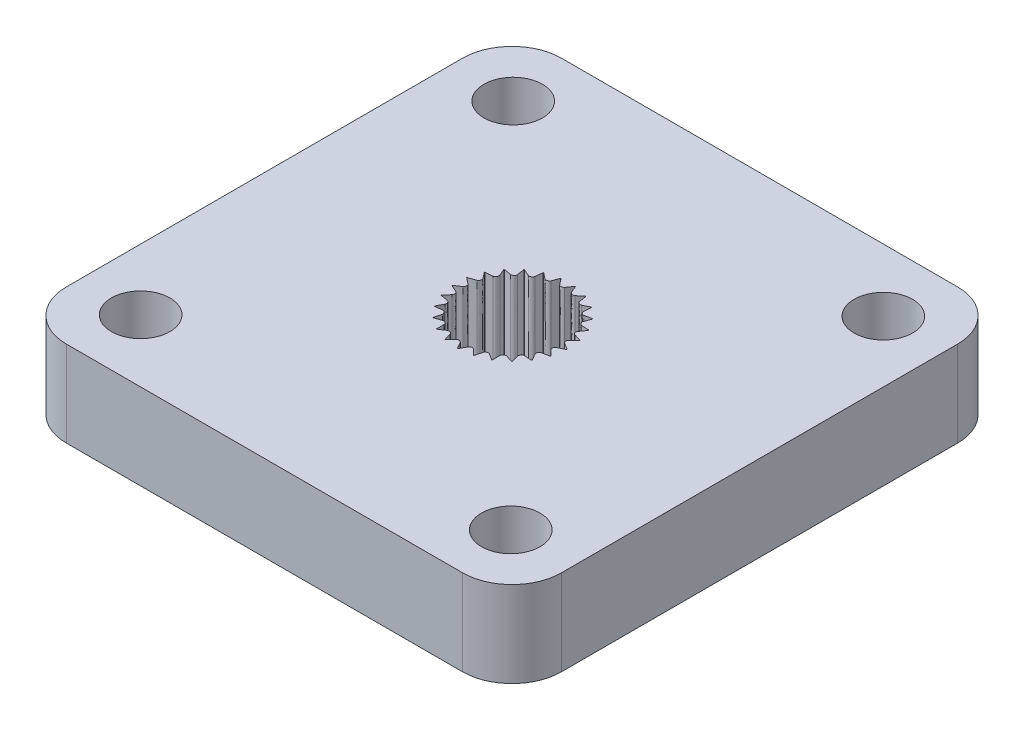
SolidWorks part; units mm, degrees
ref_plane "Front Plane" through (0, 0, 0) normal (0, 0, 1) x (1, 0, 0)
ref_plane "Top Plane" through (0, 0, 0) normal (0, 1, 0) x (1, 0, 0)
ref_plane "Right Plane" through (0, 0, 0) normal (1, 0, 0) x (0, 0, -1)
sketch "Sketch1" plane through (0, 0, 0) normal (0, 1, 0) x (1, 0, 0)
  line L1 (0, 0) -> (50.2429, 0)
  line L2 (0, 0) -> (0, 34.9455)
  line L3 (0, 34.9455) -> (50.2429, 34.9455)
  line L4 (50.2429, 0) -> (50.2429, 34.9455)
  line L5 (0, 0) -> (50.2429, 34.9455) construction
  line L6 (0, 34.9455) -> (50.2429, 0) construction
  point P4 (25.1215, 17.4728)
extrude "Boss-Extrude1" add sketch "Sketch1" along normal blind 4.4
extrude "Cut-Extrude2" cut sketch "Sketch4" against normal through all flip side to cut
sketch "Sketch4" plane through (166.0463, 0, -236.0281) normal (0, -1, 0) x (0, 0, 1)
  line L1 (208.0298, 152.713) -> (233.4298, 152.713)
  line L2 (208.0298, 152.713) -> (208.0298, 127.313)
  line L3 (208.0298, 127.313) -> (233.4298, 127.313)
  line L4 (233.4298, 152.713) -> (233.4298, 127.313)
  line L5 (208.0298, 152.713) -> (233.4298, 127.313) construction
  line L6 (208.0298, 127.313) -> (233.4298, 152.713) construction
  point P0 (220.7298, 140.013)
  point P6 (220.7298, 140.013)
fillet "Fillet1" radius 2.54 4 edges at (38.7333, 2.2, -2.5983) (13.3333, 2.2, -2.5983) (38.7333, 2.2, -27.9983) (13.3333, 2.2, -27.9983)
extrude "Cut-Extrude5" cut sketch "Sketch8" against normal through all
sketch "Sketch8" plane through (166.0463, 4.4, 928.4707) normal (0, 1, 0) x (0, 0, -1)
  circle A4 centre (934.213, 130.5192) radius 1.5
  circle A5 centre (953.2629, 130.457) radius 1.5
  circle A6 centre (934.2752, 149.5691) radius 1.5
  circle A7 centre (953.3251, 149.5069) radius 1.5
extrude "Cut-Extrude15" cut sketch "Sketch18" against normal through all and the other way through all contours S310 S311 L17 L18 L21 S146 L22 L38 L39 S147 S148 S149 L43 S150 S232 S233 L44 S235 S236 S237 L46 S239 S240 S241 S242 S243 S244 S245 S246 S247 S248 S249 S250 S251 S252 S253 S254 S255 S256 S257 S258 S259 L47 S260 S261 S262 L52 S263 S264 S265 L53
sketch "Sketch18" plane through (170.1582, 0, -5.4879) normal (0, -1, 0) x (0, 0, 1)
  line L0 (-8.9191, 146.9066) -> (-9.2331, 146.6211)
  line L1 (-9.6448, 147.0479) -> (-9.8788, 146.6937)
  line L2 (-10.3828, 147.0042) -> (-10.5223, 146.6034)
  line L3 (-12.4352, 144.0663) -> (-12.7769, 143.8287)
  line L4 (-12.3448, 143.423) -> (-12.6158, 143.1072)
  line L5 (-12.0972, 142.8224) -> (-12.2804, 142.4485)
  line L6 (-11.1062, 141.4416) -> (-10.7643, 141.6794)
  line L7 (-10.404, 141.2106) -> (-10.133, 141.5263)
  line L12 (-9.6665, 141.1614) -> (-9.4834, 141.5351)
  line L13 (-7.2766, 144.4621) -> (-6.9625, 144.7477)
  line L14 (-7.4468, 145.0892) -> (-7.2127, 145.4433)
  line L15 (-7.7676, 145.6543) -> (-7.6281, 146.0549)
  line L16 (-8.7558, 146.4912) -> (-8.7333, 146.5199)
  line L17 (-7.8155, 145.671) -> (-7.686, 146.0432)
  line L18 (-7.7007, 146.0594) -> (-7.686, 146.0432)
  line L21 (-8.0827, 145.9662) -> (-7.7007, 146.0594)
  line L22 (-8.2695, 146.1262) -> (-8.2358, 146.5183)
  line L23 (-8.6257, 146.3902) -> (-8.2513, 146.5893)
  line L25 (-10.4149, 147.0375) -> (-10.564, 146.609) construction
  line L26 (-12.4579, 144.097) -> (-12.8238, 143.8425) construction
  line L27 (-12.3771, 143.4451) -> (-12.6672, 143.107) construction
  line L28 (-12.1366, 142.8337) -> (-12.3326, 142.4335) construction
  line L29 (-11.0949, 141.3721) -> (-10.729, 141.6267) construction
  line L30 (-10.3783, 141.1442) -> (-10.0881, 141.4822) construction
  line L31 (-9.6275, 141.1015) -> (-9.4315, 141.5017) construction
  line L32 (-7.2361, 144.4135) -> (-6.9003, 144.7188) construction
  line L33 (-7.3981, 145.0502) -> (-7.1478, 145.4289) construction
  line L34 (-7.7133, 145.6266) -> (-7.5642, 146.0551) construction
  line L35 (-8.7158, 146.4598) -> (-8.6933, 146.4885) construction
  line L36 (-9.6647, 147.0894) -> (-9.9149, 146.7107) construction
  line L37 (-8.9252, 146.953) -> (-9.261, 146.6477) construction
  line L38 (-8.2541, 146.5303) -> (-8.2358, 146.5183)
  line L39 (-8.6019, 146.3454) -> (-8.2541, 146.5303)
  line L40 (-8.2188, 146.1219) -> (-8.1826, 146.544)
  line L43 (-8.9069, 146.849) -> (-9.1989, 146.5835)
  line L44 (-9.6188, 146.9951) -> (-9.8365, 146.6657)
  line L45 (-8.0948, 146.0155) -> (-7.6834, 146.1159)
  line L46 (-10.3446, 146.9595) -> (-10.4743, 146.5867)
  line L47 (-12.4062, 144.0247) -> (-12.7234, 143.804)
  line L49 (-8.2513, 146.5893) -> (-8.1826, 146.544)
  line L51 (-7.6834, 146.1159) -> (-7.6281, 146.0549)
  line L52 (-12.3062, 143.3899) -> (-12.5579, 143.0967)
  line L53 (-12.0516, 142.8) -> (-12.2217, 142.4528)
  line L54 (-11.1108, 141.5002) -> (-10.7934, 141.7211)
  line L55 (-10.4232, 141.2662) -> (-10.1715, 141.5594)
  line L56 (-9.699, 141.2105) -> (-9.529, 141.5574)
  line L57 (-7.3108, 144.4997) -> (-7.0186, 144.7653)
  line L58 (-7.4891, 145.1172) -> (-7.2715, 145.4465)
  ellipse E1 centre (-9.8345, 144.0943) end of major axis (-12.1937, 145.9474) minor radius 2.9998 (-8.7897, 146.9063) -> (-8.9252, 146.953) ccw construction
  ellipse E26 centre (-9.8345, 144.0943) end of major axis (-7.4752, 142.2412) minor radius 2.9998 (-11.649, 146.4833) -> (-11.761, 146.394) ccw construction
  ellipse E27 centre (-9.8345, 144.0943) end of major axis (-12.1937, 145.9474) minor radius 2.9998 (-12.1861, 145.9571) -> (-12.2724, 145.8426) ccw construction
  ellipse E28 centre (-9.8345, 144.0943) end of major axis (-12.1937, 145.9474) minor radius 2.9998 (-12.5754, 145.3137) -> (-12.6305, 145.1815) ccw construction
  ellipse E29 centre (-9.8345, 144.0943) end of major axis (-12.1937, 145.9474) minor radius 2.9998 (-12.7925, 144.5938) -> (-12.813, 144.452) ccw construction
  ellipse E30 centre (-9.8345, 144.0943) end of major axis (-12.1937, 145.9474) minor radius 2.9998 (-12.8238, 143.8425) -> (-12.8084, 143.7) ccw construction
  ellipse E31 centre (-9.8345, 144.0943) end of major axis (-12.1937, 145.9474) minor radius 2.9998 (-12.6672, 143.107) -> (-12.6168, 142.9729) ccw construction
  ellipse E32 centre (-9.8345, 144.0943) end of major axis (-12.1937, 145.9474) minor radius 2.9998 (-12.3326, 142.4335) -> (-12.2505, 142.3161) ccw construction
  ellipse E33 centre (-9.8345, 144.0943) end of major axis (-7.4752, 142.2412) minor radius 2.9998 (-11.8411, 141.8644) -> (-11.7323, 141.7711) ccw construction
  ellipse E34 centre (-9.8345, 144.0943) end of major axis (-12.1937, 145.9474) minor radius 2.9998 (-11.2235, 141.4354) -> (-11.0949, 141.3721) ccw construction
  ellipse E35 centre (-9.8345, 144.0943) end of major axis (-12.1937, 145.9474) minor radius 2.9998 (-10.5186, 141.1735) -> (-10.3783, 141.1442) ccw construction
  ellipse E36 centre (-9.8345, 144.0943) end of major axis (-12.1937, 145.9474) minor radius 2.9998 (-9.7707, 141.0951) -> (-9.6275, 141.1015) ccw construction
  ellipse E37 centre (-9.8345, 144.0943) end of major axis (-12.1937, 145.9474) minor radius 2.9998 (-9.0268, 141.2051) -> (-8.8898, 141.247) ccw construction
  ellipse E38 centre (-9.8345, 144.0943) end of major axis (-12.1937, 145.9474) minor radius 2.9998 (-8.3337, 141.4967) -> (-8.2113, 141.5713) ccw construction
  ellipse E39 centre (-9.8345, 144.0943) end of major axis (-7.4752, 142.2412) minor radius 2.9998 (-7.7348, 141.9515) -> (-7.6349, 142.0542) ccw construction
  ellipse E40 centre (-9.8345, 144.0943) end of major axis (-7.4752, 142.2412) minor radius 2.9998 (-7.2679, 142.541) -> (-7.1967, 142.6653) ccw construction
  ellipse E41 centre (-9.8345, 144.0943) end of major axis (-7.4752, 142.2412) minor radius 2.9998 (-6.9623, 143.228) -> (-6.9242, 143.3661) ccw construction
  ellipse E42 centre (-9.8345, 144.0943) end of major axis (-12.1937, 145.9474) minor radius 2.9998 (-6.8371, 143.9695) -> (-6.8346, 144.1127) ccw construction
  ellipse E43 centre (-9.8345, 144.0943) end of major axis (-12.1937, 145.9474) minor radius 2.9998 (-6.9003, 144.7188) -> (-6.9335, 144.8582) ccw construction
  ellipse E44 centre (-9.8345, 144.0943) end of major axis (-12.1937, 145.9474) minor radius 2.9998 (-7.1478, 145.4289) -> (-7.2146, 145.5556) ccw construction
  ellipse E45 centre (-9.8345, 144.0943) end of major axis (-12.1937, 145.9474) minor radius 2.9998 (-7.5642, 146.0551) -> (-7.6604, 146.1613) ccw construction
  ellipse E46 centre (-9.8345, 144.0943) end of major axis (-12.1937, 145.9474) minor radius 2.9998 (-8.1232, 146.5581) -> (-8.2428, 146.637) ccw construction
  ellipse E47 centre (-9.8345, 144.0943) end of major axis (-12.1937, 145.9474) minor radius 2.9998 (-10.9979, 146.8595) -> (-11.1286, 146.8008) ccw construction
  ellipse E48 centre (-9.8345, 144.0943) end of major axis (-7.4752, 142.2412) minor radius 2.9998 (-10.2737, 147.0619) -> (-10.4149, 147.0375) ccw construction
  ellipse E49 centre (-9.8345, 144.0943) end of major axis (-12.1937, 145.9474) minor radius 2.9998 (-9.5219, 147.0778) -> (-9.6647, 147.0894) ccw construction
  spline S2 degree 3 poles (-10.729, 141.6267) (-10.7247, 141.6297) (-10.7196, 141.6322) (-10.7139, 141.6338) (-10.7098, 141.6349) (-10.7053, 141.6355) (-10.7007, 141.6355) (-10.6968, 141.6355) (-10.6927, 141.6351) (-10.6888, 141.6341) (-10.6848, 141.6332) (-10.6809, 141.6317) (-10.6773, 141.6298) (-10.6738, 141.628) (-10.6706, 141.6258) (-10.6678, 141.6234) (-10.664, 141.6201) (-10.6608, 141.6163) (-10.6583, 141.6125) (-10.6557, 141.6085) (-10.6538, 141.6044) (-10.6526, 141.6003) knots -0.000035 -0.000035 -0.000035 -0.000035 -0.000015 -0.000015 -0.000015 0 0 0 0.000012 0.000012 0.000012 0.000025 0.000025 0.000025 0.000036 0.000036 0.000036 0.000053 0.000053 0.000053 0.000069 0.000069 0.000069 0.000069 construction
  spline S64 degree 3 poles (-9.9958, 146.707) (-10.0896, 146.8267) (-10.182, 146.9448) (-10.2737, 147.0619) knots 0 0 0 0 0.000588 0.000588 0.000588 0.000588 construction
  spline S65 degree 3 poles (-11.1286, 146.8008) (-11.1414, 146.6518) (-11.1543, 146.5015) (-11.1674, 146.3492) knots 0 0 0 0 0.000588 0.000588 0.000588 0.000588 construction
  spline S66 degree 3 poles (-11.1674, 146.3492) (-11.1678, 146.3438) (-11.1692, 146.3382) (-11.1716, 146.3327) (-11.1734, 146.3288) (-11.1758, 146.3248) (-11.1788, 146.3212) (-11.1813, 146.3181) (-11.1843, 146.3152) (-11.1877, 146.3128) (-11.191, 146.3103) (-11.1948, 146.3082) (-11.1986, 146.3067) (-11.2022, 146.3052) (-11.206, 146.3042) (-11.2096, 146.3037) (-11.2146, 146.3029) (-11.2196, 146.3029) (-11.2241, 146.3036) (-11.2285, 146.3042) (-11.2327, 146.3054) (-11.2364, 146.307) knots 0 0 0 0 0.000021 0.000021 0.000021 0.000035 0.000035 0.000035 0.000048 0.000048 0.000048 0.00006 0.00006 0.00006 0.000072 0.000072 0.000072 0.000089 0.000089 0.000089 0.000104 0.000104 0.000104 0.000104 construction
  spline S67 degree 3 poles (-11.2364, 146.307) (-11.3757, 146.3665) (-11.513, 146.4252) (-11.649, 146.4833) knots 0 0 0 0 0.000588 0.000588 0.000588 0.000588 construction
  spline S68 degree 3 poles (-11.761, 146.394) (-11.7367, 146.2467) (-11.7121, 146.0981) (-11.6871, 145.9474) knots 0 0 0 0 0.000588 0.000588 0.000588 0.000588 construction
  spline S69 degree 3 poles (-11.6871, 145.9474) (-11.6863, 145.9421) (-11.6862, 145.9364) (-11.6872, 145.9305) (-11.6879, 145.9262) (-11.6893, 145.9218) (-11.6913, 145.9175) (-11.693, 145.9139) (-11.6952, 145.9104) (-11.6978, 145.9071) (-11.7005, 145.9039) (-11.7036, 145.901) (-11.7069, 145.8985) (-11.71, 145.8962) (-11.7134, 145.8943) (-11.7168, 145.8929) (-11.7215, 145.8909) (-11.7262, 145.8897) (-11.7308, 145.8892) (-11.7352, 145.8887) (-11.7395, 145.8888) (-11.7436, 145.8895) knots 0 0 0 0 0.000021 0.000021 0.000021 0.000035 0.000035 0.000035 0.000048 0.000048 0.000048 0.00006 0.00006 0.00006 0.000072 0.000072 0.000072 0.000089 0.000089 0.000089 0.000104 0.000104 0.000104 0.000104 construction
  spline S70 degree 3 poles (-11.7436, 145.8895) (-11.8929, 145.9122) (-12.0402, 145.9347) (-12.1861, 145.9571) knots 0 0 0 0 0.000588 0.000588 0.000588 0.000588 construction
  spline S71 degree 3 poles (-12.2724, 145.8426) (-12.2125, 145.7062) (-12.152, 145.5686) (-12.0907, 145.4291) knots 0 0 0 0 0.000588 0.000588 0.000588 0.000588 construction
  spline S72 degree 3 poles (-12.0907, 145.4291) (-12.0885, 145.4242) (-12.087, 145.4186) (-12.0866, 145.4126) (-12.0862, 145.4083) (-12.0864, 145.4037) (-12.0873, 145.3991) (-12.0881, 145.3952) (-12.0893, 145.3912) (-12.0911, 145.3874) (-12.0928, 145.3836) (-12.0951, 145.38) (-12.0977, 145.3768) (-12.1002, 145.3738) (-12.103, 145.3711) (-12.1059, 145.3689) (-12.1099, 145.3657) (-12.1142, 145.3634) (-12.1185, 145.3618) (-12.1227, 145.3602) (-12.1268, 145.3593) (-12.1309, 145.3589) knots 0 0 0 0 0.000021 0.000021 0.000021 0.000035 0.000035 0.000035 0.000048 0.000048 0.000048 0.00006 0.00006 0.00006 0.000072 0.000072 0.000072 0.000089 0.000089 0.000089 0.000104 0.000104 0.000104 0.000104 construction
  spline S73 degree 3 poles (-12.1309, 145.3589) (-12.2809, 145.3436) (-12.4289, 145.3286) (-12.5754, 145.3137) knots 0 0 0 0 0.000588 0.000588 0.000588 0.000588 construction
  spline S74 degree 3 poles (-12.6305, 145.1815) (-12.5389, 145.0644) (-12.4464, 144.9463) (-12.3526, 144.8266) knots 0 0 0 0 0.000588 0.000588 0.000588 0.000588 construction
  spline S75 degree 3 poles (-12.3526, 144.8266) (-12.3493, 144.8224) (-12.3465, 144.8174) (-12.3446, 144.8117) (-12.3432, 144.8076) (-12.3422, 144.8031) (-12.3419, 144.7984) (-12.3417, 144.7944) (-12.3419, 144.7903) (-12.3427, 144.7862) (-12.3434, 144.7821) (-12.3447, 144.778) (-12.3465, 144.7742) (-12.3481, 144.7707) (-12.3501, 144.7674) (-12.3524, 144.7645) (-12.3555, 144.7605) (-12.3591, 144.7572) (-12.3629, 144.7545) (-12.3665, 144.752) (-12.3703, 144.75) (-12.3741, 144.7486) knots 0 0 0 0 0.000021 0.000021 0.000021 0.000035 0.000035 0.000035 0.000048 0.000048 0.000048 0.00006 0.00006 0.00006 0.000072 0.000072 0.000072 0.000089 0.000089 0.000089 0.000104 0.000104 0.000104 0.000104 construction
  spline S76 degree 3 poles (-12.3741, 144.7486) (-12.5153, 144.6963) (-12.6546, 144.6448) (-12.7925, 144.5938) knots 0 0 0 0 0.000588 0.000588 0.000588 0.000588 construction
  spline S77 degree 3 poles (-12.813, 144.452) (-12.6955, 144.3616) (-12.5768, 144.2704) (-12.4565, 144.1779) knots 0 0 0 0 0.000588 0.000588 0.000588 0.000588 construction
  spline S78 degree 3 poles (-12.4565, 144.1779) (-12.4523, 144.1747) (-12.4483, 144.1705) (-12.445, 144.1655) (-12.4427, 144.1619) (-12.4406, 144.1578) (-12.4392, 144.1533) (-12.438, 144.1495) (-12.4371, 144.1454) (-12.4369, 144.1413) (-12.4366, 144.1371) (-12.4368, 144.1328) (-12.4376, 144.1288) (-12.4383, 144.1249) (-12.4394, 144.1212) (-12.4409, 144.1179) (-12.4429, 144.1132) (-12.4456, 144.1091) (-12.4485, 144.1056) (-12.4514, 144.1022) (-12.4546, 144.0994) (-12.4579, 144.097) knots 0 0 0 0 0.000021 0.000021 0.000021 0.000035 0.000035 0.000035 0.000048 0.000048 0.000048 0.00006 0.00006 0.00006 0.000072 0.000072 0.000072 0.000089 0.000089 0.000089 0.000104 0.000104 0.000104 0.000104 construction
  spline S79 degree 3 poles (-12.3958, 143.5238) (-12.3909, 143.5217) (-12.386, 143.5187) (-12.3816, 143.5146) (-12.3784, 143.5117) (-12.3754, 143.5082) (-12.3729, 143.5043) (-12.3708, 143.5009) (-12.369, 143.4971) (-12.3677, 143.4932) (-12.3664, 143.4892) (-12.3656, 143.485) (-12.3653, 143.4809) (-12.365, 143.477) (-12.3652, 143.4732) (-12.3658, 143.4695) (-12.3666, 143.4645) (-12.3681, 143.4598) (-12.3701, 143.4557) (-12.372, 143.4517) (-12.3744, 143.4482) (-12.3771, 143.4451) knots 0 0 0 0 0.000021 0.000021 0.000021 0.000035 0.000035 0.000035 0.000048 0.000048 0.000048 0.00006 0.00006 0.00006 0.000072 0.000072 0.000072 0.000089 0.000089 0.000089 0.000104 0.000104 0.000104 0.000104 construction
  spline S80 degree 3 poles (-12.8084, 143.7) (-12.6723, 143.6419) (-12.535, 143.5832) (-12.3958, 143.5238) knots 0 0 0 0 0.000588 0.000588 0.000588 0.000588 construction
  spline S81 degree 3 poles (-12.6168, 142.9729) (-12.4709, 142.9505) (-12.3236, 142.928) (-12.1743, 142.9053) knots 0 0 0 0 0.000588 0.000588 0.000588 0.000588 construction
  spline S82 degree 3 poles (-12.1743, 142.9053) (-12.169, 142.9045) (-12.1636, 142.9028) (-12.1583, 142.9) (-12.1545, 142.8979) (-12.1508, 142.8953) (-12.1473, 142.8921) (-12.1445, 142.8894) (-12.1418, 142.8862) (-12.1395, 142.8827) (-12.1373, 142.8792) (-12.1354, 142.8753) (-12.1341, 142.8714) (-12.1329, 142.8677) (-12.1321, 142.8639) (-12.1318, 142.8602) (-12.1313, 142.8552) (-12.1316, 142.8502) (-12.1325, 142.8457) (-12.1334, 142.8414) (-12.1348, 142.8373) (-12.1366, 142.8337) knots 0 0 0 0 0.000021 0.000021 0.000021 0.000035 0.000035 0.000035 0.000048 0.000048 0.000048 0.00006 0.00006 0.00006 0.000072 0.000072 0.000072 0.000089 0.000089 0.000089 0.000104 0.000104 0.000104 0.000104 construction
  spline S83 degree 3 poles (-12.2505, 142.3161) (-12.1039, 142.331) (-11.956, 142.346) (-11.8059, 142.3613) knots 0 0 0 0 0.000588 0.000588 0.000588 0.000588 construction
  spline S84 degree 3 poles (-11.8059, 142.3613) (-11.8043, 142.3614) (-11.8025, 142.3615) (-11.8008, 142.3615) (-11.7959, 142.3615) (-11.7907, 142.3608) (-11.7855, 142.3591) (-11.7816, 142.3578) (-11.7775, 142.3559) (-11.7737, 142.3535) (-11.7698, 142.351) (-11.7661, 142.3478) (-11.763, 142.3442) (-11.7604, 142.3412) (-11.7581, 142.3378) (-11.7562, 142.3343) (-11.7544, 142.3308) (-11.7531, 142.3272) (-11.7522, 142.3237) (-11.7508, 142.3184) (-11.7504, 142.3131) (-11.7507, 142.3082) (-11.7509, 142.3058) (-11.7512, 142.3035) (-11.7516, 142.3013) knots -0.000007 -0.000007 -0.000007 -0.000007 0 0 0 0.000018 0.000018 0.000018 0.000032 0.000032 0.000032 0.000047 0.000047 0.000047 0.000059 0.000059 0.000059 0.000071 0.000071 0.000071 0.000089 0.000089 0.000089 0.000098 0.000098 0.000098 0.000098 construction
  spline S85 degree 3 poles (-11.7516, 142.3013) (-11.7818, 142.1539) (-11.8116, 142.0085) (-11.8411, 141.8644) knots 0 0 0 0 0.000588 0.000588 0.000588 0.000588 construction
  spline S86 degree 3 poles (-11.7323, 141.7711) (-11.5944, 141.8222) (-11.4551, 141.8737) (-11.3139, 141.9259) knots 0 0 0 0 0.000588 0.000588 0.000588 0.000588 construction
  spline S87 degree 3 poles (-11.3139, 141.9259) (-11.3087, 141.9279) (-11.3028, 141.929) (-11.2966, 141.929) (-11.2925, 141.929) (-11.2882, 141.9285) (-11.2839, 141.9274) (-11.2795, 141.9262) (-11.2751, 141.9244) (-11.271, 141.922) (-11.2674, 141.9199) (-11.264, 141.9172) (-11.2611, 141.9144) (-11.2584, 141.9116) (-11.256, 141.9086) (-11.254, 141.9055) (-11.2512, 141.9011) (-11.2493, 141.8964) (-11.248, 141.8918) (-11.2471, 141.8883) (-11.2465, 141.8848) (-11.2464, 141.8814) knots -0.000022 -0.000022 -0.000022 -0.000022 0 0 0 0.000014 0.000014 0.000014 0.000028 0.000028 0.000028 0.000041 0.000041 0.000041 0.000053 0.000053 0.000053 0.00007 0.00007 0.00007 0.000083 0.000083 0.000083 0.000083 construction
  spline S88 degree 3 poles (-11.2464, 141.8814) (-11.2387, 141.7309) (-11.231, 141.5825) (-11.2235, 141.4354) knots 0 0 0 0 0.000588 0.000588 0.000588 0.000588 construction
  spline S89 degree 3 poles (-10.6526, 141.6003) (-10.6074, 141.4563) (-10.5628, 141.3142) (-10.5186, 141.1735) knots 0 0 0 0 0.000588 0.000588 0.000588 0.000588 construction
  spline S90 degree 3 poles (-10.0881, 141.4822) (-10.0847, 141.4862) (-10.0804, 141.4899) (-10.0752, 141.4929) (-10.0715, 141.495) (-10.0673, 141.4968) (-10.0628, 141.4979) (-10.0589, 141.4989) (-10.0547, 141.4995) (-10.0505, 141.4995) (-10.0463, 141.4995) (-10.042, 141.499) (-10.0379, 141.4979) (-10.0339, 141.4969) (-10.03, 141.4954) (-10.0266, 141.4935) (-10.022, 141.4911) (-10.018, 141.488) (-10.0147, 141.4848) (-10.0119, 141.4819) (-10.0095, 141.4789) (-10.0075, 141.4757) knots -0.000048 -0.000048 -0.000048 -0.000048 -0.000027 -0.000027 -0.000027 -0.000013 -0.000013 -0.000013 0 0 0 0.000013 0.000013 0.000013 0.000025 0.000025 0.000025 0.000042 0.000042 0.000042 0.000056 0.000056 0.000056 0.000056 construction
  spline S91 degree 3 poles (-10.0075, 141.4757) (-9.9463, 141.3773) (-9.8857, 141.2799) (-9.8256, 141.1833) (-9.8072, 141.1538) (-9.7889, 141.1244) (-9.7707, 141.0951) knots 0 0 0 0 0.000451 0.000451 0.000451 0.000588 0.000588 0.000588 0.000588 construction
  spline S92 degree 3 poles (-9.3518, 141.5155) (-9.2421, 141.4107) (-9.134, 141.3074) (-9.0268, 141.2051) knots 0 0 0 0 0.000588 0.000588 0.000588 0.000588 construction
  spline S93 degree 3 poles (-9.4315, 141.5017) (-9.4291, 141.5065) (-9.4259, 141.5111) (-9.4217, 141.5153) (-9.4186, 141.5182) (-9.415, 141.521) (-9.4108, 141.5233) (-9.4074, 141.5252) (-9.4035, 141.5267) (-9.3995, 141.5278) (-9.3954, 141.5289) (-9.3911, 141.5294) (-9.3869, 141.5294) (-9.382, 141.5295) (-9.3771, 141.5287) (-9.3728, 141.5275) (-9.3684, 141.5262) (-9.3644, 141.5245) (-9.3609, 141.5224) (-9.3574, 141.5203) (-9.3544, 141.518) (-9.3518, 141.5155) knots -0.000061 -0.000061 -0.000061 -0.000061 -0.00004 -0.00004 -0.00004 -0.000025 -0.000025 -0.000025 -0.000013 -0.000013 -0.000013 0 0 0 0.000015 0.000015 0.000015 0.00003 0.00003 0.00003 0.000044 0.000044 0.000044 0.000044 construction
  spline S94 degree 3 poles (-8.8898, 141.247) (-8.8603, 141.391) (-8.8305, 141.5364) (-8.8003, 141.6839) knots 0 0 0 0 0.000588 0.000588 0.000588 0.000588 construction
  spline S95 degree 3 poles (-8.8003, 141.6839) (-8.7992, 141.6891) (-8.7973, 141.6944) (-8.7942, 141.6995) (-8.792, 141.7031) (-8.7891, 141.7067) (-8.7857, 141.7099) (-8.7828, 141.7126) (-8.7795, 141.7151) (-8.7759, 141.7171) (-8.7722, 141.7191) (-8.7682, 141.7208) (-8.7642, 141.7218) (-8.7605, 141.7228) (-8.7566, 141.7234) (-8.7529, 141.7235) (-8.7525, 141.7235) (-8.7521, 141.7235) (-8.7516, 141.7235) (-8.7458, 141.7235) (-8.7403, 141.7226) (-8.7354, 141.7209) (-8.7322, 141.7199) (-8.7292, 141.7186) (-8.7265, 141.717) knots -0.000074 -0.000074 -0.000074 -0.000074 -0.000053 -0.000053 -0.000053 -0.000038 -0.000038 -0.000038 -0.000026 -0.000026 -0.000026 -0.000013 -0.000013 -0.000013 -0.000001 -0.000001 -0.000001 0 0 0 0.000019 0.000019 0.000019 0.000031 0.000031 0.000031 0.000031 construction
  spline S96 degree 3 poles (-8.7265, 141.717) (-8.594, 141.6427) (-8.4632, 141.5693) (-8.3337, 141.4967) knots 0 0 0 0 0.000588 0.000588 0.000588 0.000588 construction
  spline S97 degree 3 poles (-8.2113, 141.5713) (-8.2189, 141.7184) (-8.2265, 141.8668) (-8.2342, 142.0173) knots 0 0 0 0 0.000588 0.000588 0.000588 0.000588 construction
  spline S98 degree 3 poles (-8.2342, 142.0173) (-8.2345, 142.0226) (-8.2339, 142.0283) (-8.2322, 142.0339) (-8.231, 142.038) (-8.2292, 142.0422) (-8.2266, 142.0462) (-8.2245, 142.0495) (-8.2219, 142.0527) (-8.2189, 142.0556) (-8.2159, 142.0585) (-8.2124, 142.061) (-8.2088, 142.063) (-8.2054, 142.0649) (-8.2018, 142.0664) (-8.1983, 142.0675) (-8.1936, 142.0688) (-8.1889, 142.0694) (-8.1845, 142.0695) (-8.1798, 142.0695) (-8.1752, 142.0689) (-8.171, 142.0678) knots -0.000088 -0.000088 -0.000088 -0.000088 -0.000067 -0.000067 -0.000067 -0.000053 -0.000053 -0.000053 -0.00004 -0.00004 -0.00004 -0.000027 -0.000027 -0.000027 -0.000016 -0.000016 -0.000016 0 0 0 0.000017 0.000017 0.000017 0.000017 construction
  spline S99 degree 3 poles (-8.171, 142.0678) (-8.0239, 142.0285) (-7.8787, 141.9898) (-7.7348, 141.9515) knots 0 0 0 0 0.000588 0.000588 0.000588 0.000588 construction
  spline S100 degree 3 poles (-7.6349, 142.0542) (-7.6791, 142.1949) (-7.7237, 142.337) (-7.7689, 142.481) knots 0 0 0 0 0.000588 0.000588 0.000588 0.000588 construction
  spline S101 degree 3 poles (-7.7689, 142.481) (-7.7705, 142.4861) (-7.7714, 142.4917) (-7.7711, 142.4977) (-7.771, 142.5019) (-7.7702, 142.5064) (-7.7688, 142.5109) (-7.7676, 142.5147) (-7.7658, 142.5184) (-7.7636, 142.522) (-7.7614, 142.5255) (-7.7587, 142.5288) (-7.7557, 142.5317) (-7.7529, 142.5344) (-7.7498, 142.5367) (-7.7466, 142.5386) (-7.7422, 142.5412) (-7.7375, 142.543) (-7.733, 142.5441) (-7.729, 142.5451) (-7.7251, 142.5456) (-7.7213, 142.5456) (-7.7209, 142.5456) (-7.7206, 142.5456) (-7.7202, 142.5456) knots -0.000104 -0.000104 -0.000104 -0.000104 -0.000084 -0.000084 -0.000084 -0.000068 -0.000068 -0.000068 -0.000056 -0.000056 -0.000056 -0.000043 -0.000043 -0.000043 -0.000031 -0.000031 -0.000031 -0.000015 -0.000015 -0.000015 0 0 0 0.000001 0.000001 0.000001 0.000001 construction
  spline S102 degree 3 poles (-7.7202, 142.5456) (-7.5676, 142.544) (-7.4171, 142.5425) (-7.2679, 142.541) knots 0 0 0 0 0.000588 0.000588 0.000588 0.000588 construction
  spline S103 degree 3 poles (-7.1967, 142.6653) (-7.2748, 142.7908) (-7.3536, 142.9174) (-7.4335, 143.0459) knots 0 0 0 0 0.000588 0.000588 0.000588 0.000588 construction
  spline S104 degree 3 poles (-7.4335, 143.0459) (-7.4363, 143.0504) (-7.4386, 143.0557) (-7.4398, 143.0615) (-7.4408, 143.0657) (-7.4412, 143.0702) (-7.4409, 143.0749) (-7.4406, 143.0788) (-7.4399, 143.0829) (-7.4386, 143.0869) (-7.4374, 143.0909) (-7.4356, 143.0948) (-7.4334, 143.0983) (-7.4313, 143.1016) (-7.4289, 143.1046) (-7.4262, 143.1072) (-7.4226, 143.1108) (-7.4186, 143.1138) (-7.4145, 143.116) (-7.4105, 143.1181) (-7.4064, 143.1196) (-7.4024, 143.1206) knots 0 0 0 0 0.000021 0.000021 0.000021 0.000035 0.000035 0.000035 0.000048 0.000048 0.000048 0.00006 0.00006 0.00006 0.000072 0.000072 0.000072 0.000089 0.000089 0.000089 0.000104 0.000104 0.000104 0.000104 construction
  spline S105 degree 3 poles (-7.4024, 143.1206) (-7.2539, 143.1568) (-7.1075, 143.1925) (-6.9623, 143.228) knots 0 0 0 0 0.000588 0.000588 0.000588 0.000588 construction
  spline S106 degree 3 poles (-7.2492, 143.6764) (-7.253, 143.6801) (-7.2565, 143.6847) (-7.2592, 143.69) (-7.2611, 143.6938) (-7.2627, 143.6981) (-7.2635, 143.7027) (-7.2643, 143.7066) (-7.2646, 143.7108) (-7.2644, 143.7149) (-7.2641, 143.7191) (-7.2634, 143.7233) (-7.2621, 143.7272) (-7.2609, 143.731) (-7.2593, 143.7345) (-7.2574, 143.7377) (-7.2548, 143.7421) (-7.2516, 143.7459) (-7.2482, 143.749) (-7.2449, 143.7521) (-7.2413, 143.7546) (-7.2376, 143.7565) knots 0 0 0 0 0.000021 0.000021 0.000021 0.000035 0.000035 0.000035 0.000048 0.000048 0.000048 0.00006 0.00006 0.00006 0.000072 0.000072 0.000072 0.000089 0.000089 0.000089 0.000104 0.000104 0.000104 0.000104 construction
  spline S107 degree 3 poles (-6.9242, 143.3661) (-7.0314, 143.4684) (-7.1396, 143.5717) (-7.2492, 143.6764) knots 0 0 0 0 0.000588 0.000588 0.000588 0.000588 construction
  spline S108 degree 3 poles (-7.2376, 143.7565) (-7.1025, 143.8283) (-6.9692, 143.8992) (-6.8371, 143.9695) knots 0 0 0 0 0.000588 0.000588 0.000588 0.000588 construction
  spline S109 degree 3 poles (-6.8346, 144.1127) (-6.9642, 144.1854) (-7.0949, 144.2587) (-7.2274, 144.333) knots 0 0 0 0 0.000588 0.000588 0.000588 0.000588 construction
  spline S110 degree 3 poles (-7.2274, 144.333) (-7.2321, 144.3356) (-7.2366, 144.3392) (-7.2405, 144.3437) (-7.2433, 144.3469) (-7.2459, 144.3507) (-7.2479, 144.355) (-7.2496, 144.3585) (-7.251, 144.3625) (-7.2518, 144.3665) (-7.2526, 144.3706) (-7.2529, 144.3749) (-7.2526, 144.379) (-7.2524, 144.3829) (-7.2517, 144.3868) (-7.2507, 144.3903) (-7.2492, 144.3952) (-7.2471, 144.3997) (-7.2445, 144.4036) (-7.2421, 144.4074) (-7.2392, 144.4107) (-7.2361, 144.4135) knots 0 0 0 0 0.000021 0.000021 0.000021 0.000035 0.000035 0.000035 0.000048 0.000048 0.000048 0.00006 0.00006 0.00006 0.000072 0.000072 0.000072 0.000089 0.000089 0.000089 0.000104 0.000104 0.000104 0.000104 construction
  spline S111 degree 3 poles (-6.9335, 144.8582) (-7.0773, 144.8965) (-7.2225, 144.9352) (-7.3696, 144.9744) knots 0 0 0 0 0.000588 0.000588 0.000588 0.000588 construction
  spline S112 degree 3 poles (-7.3696, 144.9744) (-7.3748, 144.9758) (-7.3801, 144.9781) (-7.385, 144.9815) (-7.3886, 144.9839) (-7.392, 144.987) (-7.395, 144.9906) (-7.3975, 144.9936) (-7.3998, 144.9971) (-7.4016, 145.0009) (-7.4034, 145.0046) (-7.4048, 145.0087) (-7.4055, 145.0127) (-7.4063, 145.0166) (-7.4066, 145.0205) (-7.4064, 145.0241) (-7.4063, 145.0293) (-7.4053, 145.0342) (-7.4038, 145.0386) (-7.4023, 145.0428) (-7.4004, 145.0467) (-7.3981, 145.0502) knots 0 0 0 0 0.000021 0.000021 0.000021 0.000035 0.000035 0.000035 0.000048 0.000048 0.000048 0.00006 0.00006 0.00006 0.000072 0.000072 0.000072 0.000089 0.000089 0.000089 0.000104 0.000104 0.000104 0.000104 construction
  spline S113 degree 3 poles (-7.2146, 145.5556) (-7.3638, 145.5571) (-7.5143, 145.5587) (-7.6669, 145.5603) knots 0 0 0 0 0.000588 0.000588 0.000588 0.000588 construction
  spline S114 degree 3 poles (-7.6669, 145.5603) (-7.6723, 145.5603) (-7.678, 145.5613) (-7.6836, 145.5633) (-7.6876, 145.5648) (-7.6917, 145.5669) (-7.6955, 145.5697) (-7.6987, 145.572) (-7.7018, 145.5748) (-7.7045, 145.578) (-7.7072, 145.5812) (-7.7095, 145.5848) (-7.7113, 145.5885) (-7.7129, 145.592) (-7.7142, 145.5957) (-7.715, 145.5993) (-7.716, 145.6043) (-7.7163, 145.6093) (-7.7159, 145.6139) (-7.7156, 145.6184) (-7.7147, 145.6227) (-7.7133, 145.6266) knots 0 0 0 0 0.000021 0.000021 0.000021 0.000035 0.000035 0.000035 0.000048 0.000048 0.000048 0.00006 0.00006 0.00006 0.000072 0.000072 0.000072 0.000089 0.000089 0.000089 0.000104 0.000104 0.000104 0.000104 construction
  spline S115 degree 3 poles (-7.6604, 146.1613) (-7.8056, 146.1258) (-7.952, 146.0901) (-8.1005, 146.0538) knots 0 0 0 0 0.000588 0.000588 0.000588 0.000588 construction
  spline S116 degree 3 poles (-8.1005, 146.0538) (-8.1057, 146.0526) (-8.1115, 146.0521) (-8.1174, 146.0527) (-8.1217, 146.0531) (-8.1262, 146.0541) (-8.1306, 146.0558) (-8.1343, 146.0573) (-8.138, 146.0592) (-8.1414, 146.0617) (-8.1448, 146.0641) (-8.1479, 146.067) (-8.1506, 146.0702) (-8.1531, 146.0732) (-8.1552, 146.0764) (-8.1568, 146.0797) (-8.1591, 146.0843) (-8.1606, 146.0891) (-8.1614, 146.0936) (-8.1622, 146.098) (-8.1623, 146.1024) (-8.1619, 146.1065) knots 0 0 0 0 0.000021 0.000021 0.000021 0.000035 0.000035 0.000035 0.000048 0.000048 0.000048 0.00006 0.00006 0.00006 0.000072 0.000072 0.000072 0.000089 0.000089 0.000089 0.000104 0.000104 0.000104 0.000104 construction
  spline S117 degree 3 poles (-8.1619, 146.1065) (-8.1489, 146.2589) (-8.136, 146.4091) (-8.1232, 146.5581) knots 0 0 0 0 0.000588 0.000588 0.000588 0.000588 construction
  spline S118 degree 3 poles (-8.7158, 146.4598) (-8.7408, 146.6104) (-8.7654, 146.759) (-8.7897, 146.9063) knots 0 0 0 0 0.000588 0.000588 0.000588 0.000588 construction
  spline S119 degree 3 poles (-8.6433, 146.4241) (-8.648, 146.4215) (-8.6535, 146.4196) (-8.6594, 146.4187) (-8.6637, 146.4181) (-8.6683, 146.418) (-8.6729, 146.4185) (-8.6769, 146.419) (-8.6809, 146.42) (-8.6848, 146.4215) (-8.6887, 146.423) (-8.6925, 146.4251) (-8.6958, 146.4275) (-8.699, 146.4297) (-8.7018, 146.4324) (-8.7043, 146.4352) (-8.7076, 146.439) (-8.7102, 146.4432) (-8.7121, 146.4475) (-8.714, 146.4516) (-8.7152, 146.4557) (-8.7158, 146.4598) knots 0 0 0 0 0.000021 0.000021 0.000021 0.000035 0.000035 0.000035 0.000048 0.000048 0.000048 0.00006 0.00006 0.00006 0.000072 0.000072 0.000072 0.000089 0.000089 0.000089 0.000104 0.000104 0.000104 0.000104 construction
  spline S120 degree 3 poles (-8.2428, 146.637) (-8.3749, 146.5668) (-8.5081, 146.4959) (-8.6433, 146.4241) knots 0 0 0 0 0.000588 0.000588 0.000588 0.000588 construction
  spline S121 degree 3 poles (-10.6414, 146.5854) (-10.7617, 146.6778) (-10.8803, 146.7691) (-10.9979, 146.8595) knots 0 0 0 0 0.000588 0.000588 0.000588 0.000588 construction
  spline S122 degree 3 poles (-10.564, 146.609) (-10.5658, 146.6039) (-10.5684, 146.5988) (-10.5722, 146.5941) (-10.5749, 146.5907) (-10.5782, 146.5875) (-10.582, 146.5847) (-10.5852, 146.5824) (-10.5888, 146.5803) (-10.5927, 146.5788) (-10.5966, 146.5772) (-10.6007, 146.5761) (-10.6048, 146.5756) (-10.6087, 146.5751) (-10.6125, 146.575) (-10.6162, 146.5754) (-10.6213, 146.5759) (-10.626, 146.5772) (-10.6303, 146.579) (-10.6344, 146.5807) (-10.6381, 146.5829) (-10.6414, 146.5854) knots 0 0 0 0 0.000021 0.000021 0.000021 0.000035 0.000035 0.000035 0.000048 0.000048 0.000048 0.00006 0.00006 0.00006 0.000072 0.000072 0.000072 0.000089 0.000089 0.000089 0.000104 0.000104 0.000104 0.000104 construction
  spline S123 degree 3 poles (-9.9149, 146.7107) (-9.9179, 146.7062) (-9.9218, 146.7019) (-9.9266, 146.6982) (-9.93, 146.6956) (-9.934, 146.6933) (-9.9384, 146.6915) (-9.9421, 146.6901) (-9.9461, 146.689) (-9.9502, 146.6884) (-9.9544, 146.6879) (-9.9587, 146.6879) (-9.9628, 146.6884) (-9.9666, 146.6888) (-9.9704, 146.6898) (-9.9738, 146.691) (-9.9786, 146.6928) (-9.9829, 146.6952) (-9.9866, 146.698) (-9.9902, 146.7007) (-9.9932, 146.7038) (-9.9958, 146.707) knots 0 0 0 0 0.000021 0.000021 0.000021 0.000035 0.000035 0.000035 0.000048 0.000048 0.000048 0.00006 0.00006 0.00006 0.000072 0.000072 0.000072 0.000089 0.000089 0.000089 0.000104 0.000104 0.000104 0.000104 construction
  spline S124 degree 3 poles (-9.3402, 146.6642) (-9.4015, 146.8038) (-9.462, 146.9414) (-9.5219, 147.0778) knots 0 0 0 0 0.000588 0.000588 0.000588 0.000588 construction
  spline S125 degree 3 poles (-9.261, 146.6477) (-9.265, 146.6441) (-9.2698, 146.6409) (-9.2753, 146.6385) (-9.2793, 146.6368) (-9.2837, 146.6356) (-9.2884, 146.635) (-9.2924, 146.6345) (-9.2965, 146.6344) (-9.3007, 146.6349) (-9.3048, 146.6354) (-9.309, 146.6364) (-9.3128, 146.6379) (-9.3164, 146.6394) (-9.3199, 146.6412) (-9.3229, 146.6433) (-9.3271, 146.6462) (-9.3307, 146.6496) (-9.3335, 146.6532) (-9.3363, 146.6567) (-9.3385, 146.6605) (-9.3402, 146.6642) knots 0 0 0 0 0.000021 0.000021 0.000021 0.000035 0.000035 0.000035 0.000048 0.000048 0.000048 0.00006 0.00006 0.00006 0.000072 0.000072 0.000072 0.000089 0.000089 0.000089 0.000104 0.000104 0.000104 0.000104 construction
  spline S146 degree 3 poles (-8.0827, 145.9662) (-8.1624, 145.9467) (-8.2765, 146.0445) (-8.2695, 146.1262) knots 0 0 0 0 0.000104 0.000104 0.000104 0.000104
  spline S147 degree 3 poles (-8.6019, 146.3454) (-8.6742, 146.3069) (-8.809, 146.3734) (-8.8224, 146.4542) knots 0 0 0 0 0.000104 0.000104 0.000104 0.000104
  spline S148 degree 3 poles (-8.8224, 146.4542) (-8.8438, 146.5835) (-8.8651, 146.7127) (-8.8865, 146.842) knots 0 0 0 0 0.00051 0.00051 0.00051 0.00051
  spline S149 degree 3 poles (-8.8865, 146.842) (-8.8933, 146.8443) (-8.9001, 146.8467) (-8.9069, 146.849) knots -1.240534 -1.240534 -1.240534 -1.240534 -1.233076 -1.233076 -1.233076 -1.233076
  spline S150 degree 3 poles (-9.1989, 146.5835) (-9.2596, 146.5284) (-9.4065, 146.5594) (-9.4395, 146.6344) knots 0 0 0 0 0.000104 0.000104 0.000104 0.000104
  spline S151 degree 3 poles (-8.7722, 146.4625) (-8.7953, 146.6016) (-8.8183, 146.7407) (-8.8413, 146.8798) knots 0 0 0 0 0.000549 0.000549 0.000549 0.000549
  spline S152 degree 3 poles (-8.8413, 146.8798) (-8.8671, 146.8891) (-8.893, 146.8981) (-8.9191, 146.9066) knots -1.250789 -1.250789 -1.250789 -1.250789 -1.222886 -1.222886 -1.222886 -1.222886
  spline S153 degree 3 poles (-9.2331, 146.6211) (-9.2734, 146.5845) (-9.3711, 146.605) (-9.393, 146.6548) knots 0 0 0 0 0.000104 0.000104 0.000104 0.000104
  spline S154 degree 3 poles (-9.393, 146.6548) (-9.4496, 146.7836) (-9.5062, 146.9124) (-9.5627, 147.0413) knots 0 0 0 0 0.000549 0.000549 0.000549 0.000549
  spline S155 degree 3 poles (-9.5627, 147.0413) (-9.59, 147.0438) (-9.6174, 147.0461) (-9.6448, 147.0479) knots -0.999445 -0.999445 -0.999445 -0.999445 -0.971533 -0.971533 -0.971533 -0.971533
  spline S156 degree 3 poles (-9.8788, 146.6937) (-9.9089, 146.6482) (-10.0085, 146.6438) (-10.042, 146.6867) knots 0 0 0 0 0.000104 0.000104 0.000104 0.000104
  spline S157 degree 3 poles (-10.042, 146.6867) (-10.1286, 146.7972) (-10.2151, 146.9077) (-10.3016, 147.0182) knots 0 0 0 0 0.000549 0.000549 0.000549 0.000549
  spline S158 degree 3 poles (-10.3016, 147.0182) (-10.3288, 147.0139) (-10.3558, 147.0092) (-10.3828, 147.0042) knots -0.748108 -0.748108 -0.748108 -0.748108 -0.720179 -0.720179 -0.720179 -0.720179
  spline S159 degree 3 poles (-10.5223, 146.6034) (-10.5402, 146.552) (-10.6354, 146.523) (-10.6786, 146.5561) knots 0 0 0 0 0.000104 0.000104 0.000104 0.000104
  spline S160 degree 3 poles (-10.6786, 146.5561) (-10.7896, 146.6414) (-10.9006, 146.7268) (-11.0116, 146.8121) knots 0 0 0 0 0.000549 0.000549 0.000549 0.000549
  spline S161 degree 3 poles (-11.0116, 146.8121) (-11.0368, 146.8012) (-11.0619, 146.7899) (-11.0868, 146.7783) knots -0.496777 -0.496777 -0.496777 -0.496777 -0.468827 -0.468827 -0.468827 -0.468827
  spline S162 degree 3 poles (-11.0868, 146.7783) (-11.0989, 146.6375) (-11.111, 146.4967) (-11.123, 146.3559) knots 0.000038 0.000038 0.000038 0.000038 0.000588 0.000588 0.000588 0.000588
  spline S163 degree 3 poles (-11.123, 146.3559) (-11.1277, 146.3017) (-11.2126, 146.25) (-11.2627, 146.2714) knots 0 0 0 0 0.000104 0.000104 0.000104 0.000104
  spline S164 degree 3 poles (-11.2627, 146.2714) (-11.3911, 146.3262) (-11.5195, 146.3811) (-11.6479, 146.436) knots 0 0 0 0 0.000549 0.000549 0.000549 0.000549
  spline S165 degree 3 poles (-11.6479, 146.436) (-11.6697, 146.4191) (-11.6912, 146.4019) (-11.7124, 146.3845) knots -0.245453 -0.245453 -0.245453 -0.245453 -0.217479 -0.217479 -0.217479 -0.217479
  spline S166 degree 3 poles (-11.7124, 146.3845) (-11.6894, 146.2452) (-11.6664, 146.106) (-11.6433, 145.9668) knots 0.000038 0.000038 0.000038 0.000038 0.000588 0.000588 0.000588 0.000588
  spline S167 degree 3 poles (-11.6433, 145.9668) (-11.6344, 145.9131) (-11.7037, 145.8421) (-11.7575, 145.8503) knots 0 0 0 0 0.000104 0.000104 0.000104 0.000104
  spline S168 degree 3 poles (-11.7575, 145.8503) (-11.8952, 145.8713) (-12.033, 145.8923) (-12.1707, 145.9134) knots 0 0 0 0 0.000549 0.000549 0.000549 0.000549
  spline S169 degree 3 poles (-12.1707, 145.9134) (-12.1876, 145.8916) (-12.2042, 145.8696) (-12.2204, 145.8474) knots 0.005865 0.005865 0.005865 0.005865 0.033865 0.033865 0.033865 0.033865
  spline S170 degree 3 poles (-12.2204, 145.8474) (-12.1638, 145.7185) (-12.1071, 145.5895) (-12.0505, 145.4605) knots 0.000038 0.000038 0.000038 0.000038 0.000588 0.000588 0.000588 0.000588
  spline S171 degree 3 poles (-12.0505, 145.4605) (-12.0286, 145.4108) (-12.078, 145.3248) (-12.132, 145.3193) knots 0 0 0 0 0.000104 0.000104 0.000104 0.000104
  spline S172 degree 3 poles (-12.132, 145.3193) (-12.2704, 145.3053) (-12.4088, 145.2912) (-12.5471, 145.2772) knots 0 0 0 0 0.000549 0.000549 0.000549 0.000549
  spline S173 degree 3 poles (-12.5471, 145.2772) (-12.5581, 145.2519) (-12.5686, 145.2265) (-12.5789, 145.2009) knots 0.257175 0.257175 0.257175 0.257175 0.285202 0.285202 0.285202 0.285202
  spline S174 degree 3 poles (-12.5789, 145.2009) (-12.4923, 145.0902) (-12.4056, 144.9796) (-12.3189, 144.8689) knots 0.000038 0.000038 0.000038 0.000038 0.000588 0.000588 0.000588 0.000588
  spline S175 degree 3 poles (-12.3189, 144.8689) (-12.2854, 144.8262) (-12.3118, 144.7308) (-12.3628, 144.712) knots 0 0 0 0 0.000104 0.000104 0.000104 0.000104
  spline S176 degree 3 poles (-12.3628, 144.712) (-12.493, 144.6638) (-12.6232, 144.6156) (-12.7535, 144.5674) knots 0 0 0 0 0.000549 0.000549 0.000549 0.000549
  spline S177 degree 3 poles (-12.7535, 144.5674) (-12.7578, 144.5402) (-12.7617, 144.5129) (-12.7653, 144.4856) knots 0.508481 0.508481 0.508481 0.508481 0.536533 0.536533 0.536533 0.536533
  spline S178 degree 3 poles (-12.7653, 144.4856) (-12.6542, 144.4001) (-12.543, 144.3146) (-12.4318, 144.2292) knots 0.000038 0.000038 0.000038 0.000038 0.000588 0.000588 0.000588 0.000588
  spline S179 degree 3 poles (-12.4318, 144.2292) (-12.3888, 144.1961) (-12.3906, 144.0974) (-12.4352, 144.0663) knots 0 0 0 0 0.000104 0.000104 0.000104 0.000104
  spline S180 degree 3 poles (-12.7769, 143.8287) (-12.7743, 143.8012) (-12.7713, 143.7737) (-12.7679, 143.7463) knots 0.759782 0.759782 0.759782 0.759782 0.787857 0.787857 0.787857 0.787857
  spline S181 degree 3 poles (-12.7679, 143.7463) (-12.6393, 143.6914) (-12.5107, 143.6364) (-12.3821, 143.5815) knots 0.000039 0.000039 0.000039 0.000039 0.000588 0.000588 0.000588 0.000588
  spline S182 degree 3 poles (-12.3821, 143.5815) (-12.3322, 143.5602) (-12.3094, 143.4642) (-12.3448, 143.423) knots 0 0 0 0 0.000104 0.000104 0.000104 0.000104
  spline S183 degree 3 poles (-12.6158, 143.1072) (-12.6064, 143.0813) (-12.5967, 143.0554) (-12.5867, 143.0297) knots 1.011082 1.011082 1.011082 1.011082 1.039175 1.039175 1.039175 1.039175
  spline S184 degree 3 poles (-12.5867, 143.0297) (-12.4487, 143.0086) (-12.3108, 142.9875) (-12.1729, 142.9665) knots 0.000039 0.000039 0.000039 0.000039 0.000588 0.000588 0.000588 0.000588
  spline S185 degree 3 poles (-12.1729, 142.9665) (-12.1193, 142.9583) (-12.0734, 142.8711) (-12.0972, 142.8224) knots 0 0 0 0 0.000104 0.000104 0.000104 0.000104
  spline S186 degree 3 poles (-12.2804, 142.4485) (-12.2649, 142.4257) (-12.249, 142.403) (-12.2329, 142.3806) knots 1.262382 1.262382 1.262382 1.262382 1.290486 1.290486 1.290486 1.290486
  spline S187 degree 3 poles (-12.2329, 142.3806) (-12.0944, 142.3947) (-11.9559, 142.4087) (-11.8174, 142.4228) knots 0.000039 0.000039 0.000039 0.000039 0.000588 0.000588 0.000588 0.000588
  spline S188 degree 3 poles (-11.8174, 142.4228) (-11.8148, 142.4231) (-11.8104, 142.4233) (-11.7538, 142.4235) (-11.6981, 142.3511) (-11.7081, 142.3021) knots -0.000007 -0.000007 -0.000007 -0.000007 -0.000002 0.000002 0.000098 0.000098 0.000098 0.000098
  spline S189 degree 3 poles (-11.7081, 142.3021) (-11.736, 142.1661) (-11.7639, 142.03) (-11.7917, 141.8939) knots 0 0 0 0 0.000549 0.000549 0.000549 0.000549
  spline S190 degree 3 poles (-11.7917, 141.8939) (-11.771, 141.8756) (-11.75, 141.8576) (-11.7288, 141.8399) knots 1.513682 1.513682 1.513682 1.513682 1.541791 1.541791 1.541791 1.541791
  spline S191 degree 3 poles (-11.7288, 141.8399) (-11.5985, 141.8882) (-11.4681, 141.9364) (-11.3378, 141.9846) knots 0.000039 0.000039 0.000039 0.000039 0.000588 0.000588 0.000588 0.000588
  spline S192 degree 3 poles (-11.3378, 141.9846) (-11.3299, 141.9875) (-11.3156, 141.9909) (-11.2538, 141.9916) (-11.204, 141.9352) (-11.2019, 141.895) knots -0.000022 -0.000022 -0.000022 -0.000022 -0.000005 0.000005 0.000083 0.000083 0.000083 0.000083
  spline S193 degree 3 poles (-11.2019, 141.895) (-11.1948, 141.7561) (-11.1877, 141.6171) (-11.1805, 141.4782) knots 0 0 0 0 0.000549 0.000549 0.000549 0.000549
  spline S194 degree 3 poles (-11.1805, 141.4782) (-11.1559, 141.4656) (-11.1311, 141.4534) (-11.1062, 141.4416) knots 1.764987 1.764987 1.764987 1.764987 1.793092 1.793092 1.793092 1.793092
  spline S195 degree 3 poles (-10.7643, 141.6794) (-10.753, 141.6873) (-10.7306, 141.6975) (-10.661, 141.6984) (-10.6197, 141.6564) (-10.6104, 141.6265) knots -0.000035 -0.000035 -0.000035 -0.000035 -0.000009 0.000009 0.000069 0.000069 0.000069 0.000069
  spline S196 degree 3 poles (-10.6104, 141.6265) (-10.5686, 141.4935) (-10.5269, 141.3605) (-10.4851, 141.2275) knots 0 0 0 0 0.00055 0.00055 0.00055 0.00055
  spline S197 degree 3 poles (-10.4851, 141.2275) (-10.4582, 141.2215) (-10.4311, 141.2158) (-10.404, 141.2106) knots 2.016296 2.016296 2.016296 2.016296 2.044392 2.044392 2.044392 2.044392
  spline S198 degree 3 poles (-10.133, 141.5263) (-10.1208, 141.5406) (-10.0922, 141.562) (-10.0157, 141.5625) (-9.9828, 141.5331) (-9.9707, 141.5136) knots -0.000048 -0.000048 -0.000048 -0.000048 -0.000012 0.000012 0.000056 0.000056 0.000056 0.000056
  spline S199 degree 3 poles (-9.9707, 141.5136) (-9.8969, 141.3949) (-9.823, 141.2763) (-9.7492, 141.1577) knots 0 0 0 0 0.00055 0.00055 0.00055 0.00055
  spline S200 degree 3 poles (-9.7492, 141.1577) (-9.7216, 141.1585) (-9.694, 141.1598) (-9.6665, 141.1614) knots 2.267611 2.267611 2.267611 2.267611 2.295692 2.295692 2.295692 2.295692
  spline S201 degree 3 poles (-9.4834, 141.5351) (-9.472, 141.5583) (-9.4369, 141.5922) (-9.3619, 141.5919) (-9.3353, 141.575) (-9.3229, 141.5632) knots -0.000061 -0.000061 -0.000061 -0.000061 -0.000011 0.000011 0.000044 0.000044 0.000044 0.000044
  spline S202 degree 3 poles (-9.3229, 141.5632) (-9.2217, 141.4664) (-9.1204, 141.3697) (-9.019, 141.273) knots 0 0 0 0 0.00055 0.00055 0.00055 0.00055
  spline S203 degree 3 poles (-9.019, 141.273) (-8.9925, 141.2807) (-8.9661, 141.2887) (-8.9399, 141.2971) knots 2.518932 2.518932 2.518932 2.518932 2.546993 2.546993 2.546993 2.546993
  spline S204 degree 3 poles (-8.9399, 141.2971) (-8.912, 141.4331) (-8.8842, 141.5691) (-8.8563, 141.7051) knots 0.000039 0.000039 0.000039 0.000039 0.000588 0.000588 0.000588 0.000588
  spline S205 degree 3 poles (-8.8563, 141.7051) (-8.8495, 141.7387) (-8.8059, 141.7861) (-8.7382, 141.7855) (-8.7184, 141.7782) (-8.7079, 141.7723) knots -0.000074 -0.000074 -0.000074 -0.000074 -0.000008 0.000008 0.000031 0.000031 0.000031 0.000031
  spline S206 degree 3 poles (-8.7079, 141.7723) (-8.5854, 141.7036) (-8.463, 141.6349) (-8.3405, 141.5663) knots 0 0 0 0 0.00055 0.00055 0.00055 0.00055
  spline S207 degree 3 poles (-8.3405, 141.5663) (-8.3167, 141.5803) (-8.2932, 141.5946) (-8.2699, 141.6093) knots 2.770261 2.770261 2.770261 2.770261 2.798297 2.798297 2.798297 2.798297
  spline S208 degree 3 poles (-8.2699, 141.6093) (-8.277, 141.7481) (-8.2842, 141.8869) (-8.2913, 142.0257) knots 0.000039 0.000039 0.000039 0.000039 0.000588 0.000588 0.000588 0.000588
  spline S209 degree 3 poles (-8.2913, 142.0257) (-8.2935, 142.0691) (-8.2421, 142.1316) (-8.1815, 142.1314) (-8.1705, 142.1295) (-8.1642, 142.1279) knots -0.000088 -0.000088 -0.000088 -0.000088 -0.000004 0.000004 0.000017 0.000017 0.000017 0.000017
  spline S210 degree 3 poles (-8.1642, 142.1279) (-8.0282, 142.0916) (-7.8922, 142.0553) (-7.7562, 142.0191) knots 0 0 0 0 0.00055 0.00055 0.00055 0.00055
  spline S211 degree 3 poles (-7.7562, 142.0191) (-7.7367, 142.0386) (-7.7175, 142.0583) (-7.6986, 142.0783) knots 3.021596 3.021596 3.021596 3.021596 3.049606 3.049606 3.049606 3.049606
  spline S212 degree 3 poles (-7.6986, 142.0783) (-7.7403, 142.2111) (-7.782, 142.344) (-7.8237, 142.4768) knots 0.000039 0.000039 0.000039 0.000039 0.000588 0.000588 0.000588 0.000588
  spline S213 degree 3 poles (-7.8237, 142.4768) (-7.8397, 142.5279) (-7.7823, 142.607) (-7.7274, 142.6074) (-7.7265, 142.6074) (-7.726, 142.6074) knots -0.000104 -0.000104 -0.000104 -0.000104 0 0 0.000001 0.000001 0.000001 0.000001
  spline S214 degree 3 poles (-7.726, 142.6074) (-7.5849, 142.606) (-7.4439, 142.6045) (-7.3028, 142.6031) knots 0 0 0 0 0.00055 0.00055 0.00055 0.00055
  spline S215 degree 3 poles (-7.3028, 142.6031) (-7.2888, 142.6267) (-7.2751, 142.6506) (-7.2618, 142.6747) knots -3.010248 -3.010248 -3.010248 -3.010248 -2.982265 -2.982265 -2.982265 -2.982265
  spline S216 degree 3 poles (-7.2618, 142.6747) (-7.3355, 142.7931) (-7.4093, 142.9116) (-7.483, 143.0301) knots 0.000039 0.000039 0.000039 0.000039 0.000588 0.000588 0.000588 0.000588
  spline S217 degree 3 poles (-7.483, 143.0301) (-7.5117, 143.0763) (-7.4736, 143.1681) (-7.4207, 143.181) knots 0 0 0 0 0.000104 0.000104 0.000104 0.000104
  spline S218 degree 3 poles (-7.4207, 143.181) (-7.2835, 143.2144) (-7.1462, 143.2479) (-7.009, 143.2814) knots 0 0 0 0 0.00055 0.00055 0.00055 0.00055
  spline S219 degree 3 poles (-7.009, 143.2814) (-7.0013, 143.3078) (-6.994, 143.3343) (-6.9871, 143.3609) knots -2.758901 -2.758901 -2.758901 -2.758901 -2.730943 -2.730943 -2.730943 -2.730943
  spline S220 degree 3 poles (-6.9871, 143.3609) (-7.0883, 143.4575) (-7.1894, 143.5541) (-7.2906, 143.6507) knots 0.000039 0.000039 0.000039 0.000039 0.000588 0.000588 0.000588 0.000588
  spline S221 degree 3 poles (-7.2906, 143.6507) (-7.3299, 143.6883) (-7.3158, 143.7868) (-7.2677, 143.8124) knots 0 0 0 0 0.000104 0.000104 0.000104 0.000104
  spline S222 degree 3 poles (-7.2677, 143.8124) (-7.1429, 143.8788) (-7.018, 143.9452) (-6.8931, 144.0116) knots 0 0 0 0 0.00055 0.00055 0.00055 0.00055
  spline S223 degree 3 poles (-6.8931, 144.0116) (-6.8922, 144.039) (-6.8917, 144.0665) (-6.8916, 144.094) knots -2.50755 -2.50755 -2.50755 -2.50755 -2.479614 -2.479614 -2.479614 -2.479614
  spline S224 degree 3 poles (-6.8916, 144.094) (-7.014, 144.1625) (-7.1363, 144.2311) (-7.2586, 144.2998) knots 0.000039 0.000039 0.000039 0.000039 0.000588 0.000588 0.000588 0.000588
  spline S225 degree 3 poles (-7.2586, 144.2998) (-7.306, 144.3264) (-7.3169, 144.4255) (-7.2766, 144.4621) knots 0 0 0 0 0.000104 0.000104 0.000104 0.000104
  spline S226 degree 3 poles (-6.9625, 144.7477) (-6.9684, 144.7744) (-6.9748, 144.8011) (-6.9815, 144.8278) knots -2.256196 -2.256196 -2.256196 -2.256196 -2.228279 -2.228279 -2.228279 -2.228279
  spline S227 degree 3 poles (-6.9815, 144.8278) (-7.1174, 144.8639) (-7.2532, 144.9001) (-7.389, 144.9364) knots 0.000039 0.000039 0.000039 0.000039 0.000588 0.000588 0.000588 0.000588
  spline S228 degree 3 poles (-7.389, 144.9364) (-7.4416, 144.9504) (-7.4768, 145.0437) (-7.4468, 145.0892) knots 0 0 0 0 0.000104 0.000104 0.000104 0.000104
  spline S229 degree 3 poles (-7.2127, 145.4433) (-7.2252, 145.4678) (-7.238, 145.4921) (-7.2511, 145.5162) knots -2.004843 -2.004843 -2.004843 -2.004843 -1.976937 -1.976937 -1.976937 -1.976937
  spline S230 degree 3 poles (-7.2511, 145.5162) (-7.392, 145.5176) (-7.5328, 145.519) (-7.6737, 145.5205) knots 0.000039 0.000039 0.000039 0.000039 0.000588 0.000588 0.000588 0.000588
  spline S231 degree 3 poles (-7.6737, 145.5205) (-7.7282, 145.5211) (-7.7855, 145.6028) (-7.7676, 145.6543) knots 0 0 0 0 0.000104 0.000104 0.000104 0.000104
  spline S232 degree 3 poles (-9.4395, 146.6344) (-9.4921, 146.754) (-9.5446, 146.8737) (-9.5972, 146.9933) knots 0 0 0 0 0.00051 0.00051 0.00051 0.00051
  spline S233 degree 3 poles (-9.5972, 146.9933) (-9.6044, 146.9939) (-9.6116, 146.9945) (-9.6188, 146.9951) knots -0.989174 -0.989174 -0.989174 -0.989174 -0.981695 -0.981695 -0.981695 -0.981695
  spline S234 degree 3 poles (-8.0948, 146.0155) (-8.1477, 146.0026) (-8.2235, 146.0676) (-8.2188, 146.1219) knots 0 0 0 0 0.000104 0.000104 0.000104 0.000104
  spline S235 degree 3 poles (-9.8365, 146.6657) (-9.8816, 146.5973) (-10.0315, 146.5909) (-10.082, 146.6554) knots 0 0 0 0 0.000104 0.000104 0.000104 0.000104
  spline S236 degree 3 poles (-10.082, 146.6554) (-10.1624, 146.758) (-10.2428, 146.8606) (-10.3231, 146.9632) knots 0 0 0 0 0.00051 0.00051 0.00051 0.00051
  spline S237 degree 3 poles (-10.3231, 146.9632) (-10.3303, 146.962) (-10.3374, 146.9608) (-10.3446, 146.9595) knots -0.737826 -0.737826 -0.737826 -0.737826 -0.730316 -0.730316 -0.730316 -0.730316
  spline S238 degree 3 poles (-8.6257, 146.3902) (-8.6738, 146.3647) (-8.7633, 146.4088) (-8.7722, 146.4625) knots 0 0 0 0 0.000104 0.000104 0.000104 0.000104
  spline S239 degree 3 poles (-10.4743, 146.5867) (-10.5012, 146.5093) (-10.6446, 146.466) (-10.7095, 146.5159) knots 0 0 0 0 0.000104 0.000104 0.000104 0.000104
  spline S240 degree 3 poles (-10.7095, 146.5159) (-10.8126, 146.595) (-10.9157, 146.6743) (-11.0187, 146.7535) knots 0 0 0 0 0.00051 0.00051 0.00051 0.00051
  spline S241 degree 3 poles (-11.0187, 146.7535) (-11.0254, 146.7505) (-11.032, 146.7476) (-11.0387, 146.7445) knots -0.486491 -0.486491 -0.486491 -0.486491 -0.478937 -0.478937 -0.478937 -0.478937
  spline S242 degree 3 poles (-11.0387, 146.7445) (-11.0499, 146.6135) (-11.0612, 146.4825) (-11.0724, 146.3515) knots 0.000077 0.000077 0.000077 0.000077 0.000588 0.000588 0.000588 0.000588
  spline S243 degree 3 poles (-11.0724, 146.3515) (-11.0794, 146.27) (-11.2073, 146.1925) (-11.2826, 146.2246) knots 0 0 0 0 0.000104 0.000104 0.000104 0.000104
  spline S244 degree 3 poles (-11.2826, 146.2246) (-11.4018, 146.2755) (-11.521, 146.3265) (-11.6403, 146.3774) knots 0 0 0 0 0.000509 0.000509 0.000509 0.000509
  spline S245 degree 3 poles (-11.6403, 146.3774) (-11.646, 146.3729) (-11.6518, 146.3683) (-11.6575, 146.3637) knots -0.235171 -0.235171 -0.235171 -0.235171 -0.227567 -0.227567 -0.227567 -0.227567
  spline S246 degree 3 poles (-11.6575, 146.3637) (-11.6361, 146.2341) (-11.6146, 146.1046) (-11.5932, 145.9751) knots 0.000077 0.000077 0.000077 0.000077 0.000588 0.000588 0.000588 0.000588
  spline S247 degree 3 poles (-11.5932, 145.9751) (-11.5798, 145.8944) (-11.6843, 145.7877) (-11.7652, 145.8) knots 0 0 0 0 0.000104 0.000104 0.000104 0.000104
  spline S248 degree 3 poles (-11.7652, 145.8) (-11.893, 145.8195) (-12.0209, 145.8391) (-12.1487, 145.8586) knots 0 0 0 0 0.000509 0.000509 0.000509 0.000509
  spline S249 degree 3 poles (-12.1487, 145.8586) (-12.1532, 145.8527) (-12.1576, 145.8468) (-12.1621, 145.8409) knots 0.016136 0.016136 0.016136 0.016136 0.023792 0.023792 0.023792 0.023792
  spline S250 degree 3 poles (-12.1621, 145.8409) (-12.1094, 145.7209) (-12.0567, 145.6009) (-12.004, 145.481) knots 0.000077 0.000077 0.000077 0.000077 0.000588 0.000588 0.000588 0.000588
  spline S251 degree 3 poles (-12.004, 145.481) (-11.9711, 145.4061) (-12.0456, 145.2771) (-12.1269, 145.2688) knots 0 0 0 0 0.000104 0.000104 0.000104 0.000104
  spline S252 degree 3 poles (-12.1269, 145.2688) (-12.2553, 145.2557) (-12.3837, 145.2427) (-12.5122, 145.2297) knots 0 0 0 0 0.000509 0.000509 0.000509 0.000509
  spline S253 degree 3 poles (-12.5122, 145.2297) (-12.5151, 145.2228) (-12.5179, 145.2159) (-12.5208, 145.2091) knots 0.26743 0.26743 0.26743 0.26743 0.275141 0.275141 0.275141 0.275141
  spline S254 degree 3 poles (-12.5208, 145.2091) (-12.4402, 145.1061) (-12.3596, 145.0032) (-12.2789, 144.9003) knots 0.000077 0.000077 0.000077 0.000077 0.000588 0.000588 0.000588 0.000588
  spline S255 degree 3 poles (-12.2789, 144.9003) (-12.2286, 144.836) (-12.2685, 144.6927) (-12.3451, 144.6643) knots 0 0 0 0 0.000104 0.000104 0.000104 0.000104
  spline S256 degree 3 poles (-12.3451, 144.6643) (-12.466, 144.6196) (-12.5869, 144.5749) (-12.7078, 144.5302) knots 0 0 0 0 0.000509 0.000509 0.000509 0.000509
  spline S257 degree 3 poles (-12.7078, 144.5302) (-12.7089, 144.5228) (-12.71, 144.5153) (-12.711, 144.5079) knots 0.518713 0.518713 0.518713 0.518713 0.526475 0.526475 0.526475 0.526475
  spline S258 degree 3 poles (-12.711, 144.5079) (-12.6076, 144.4284) (-12.5043, 144.3489) (-12.4009, 144.2695) knots 0.000077 0.000077 0.000077 0.000077 0.000588 0.000588 0.000588 0.000588
  spline S259 degree 3 poles (-12.4009, 144.2695) (-12.3361, 144.2198) (-12.3392, 144.0713) (-12.4062, 144.0247) knots 0 0 0 0 0.000104 0.000104 0.000104 0.000104
  spline S260 degree 3 poles (-12.7234, 143.804) (-12.7226, 143.7965) (-12.7218, 143.789) (-12.7209, 143.7815) knots 0.769987 0.769987 0.769987 0.769987 0.777796 0.777796 0.777796 0.777796
  spline S261 degree 3 poles (-12.7209, 143.7815) (-12.6013, 143.7304) (-12.4818, 143.6793) (-12.3622, 143.6282) knots 0.000077 0.000077 0.000077 0.000077 0.000588 0.000588 0.000588 0.000588
  spline S262 degree 3 poles (-12.3622, 143.6282) (-12.2871, 143.5962) (-12.2531, 143.4518) (-12.3062, 143.3899) knots 0 0 0 0 0.000104 0.000104 0.000104 0.000104
  spline S263 degree 3 poles (-12.5579, 143.0967) (-12.5552, 143.0896) (-12.5526, 143.0825) (-12.5499, 143.0755) knots 1.021259 1.021259 1.021259 1.021259 1.029102 1.029102 1.029102 1.029102
  spline S264 degree 3 poles (-12.5499, 143.0755) (-12.4217, 143.0559) (-12.2935, 143.0363) (-12.1653, 143.0167) knots 0.000077 0.000077 0.000077 0.000077 0.000588 0.000588 0.000588 0.000588
  spline S265 degree 3 poles (-12.1653, 143.0167) (-12.0846, 143.0044) (-12.0157, 142.8733) (-12.0516, 142.8) knots 0 0 0 0 0.000104 0.000104 0.000104 0.000104
  spline S266 degree 3 poles (-12.2217, 142.4528) (-12.2174, 142.4466) (-12.213, 142.4404) (-12.2086, 142.4342) knots 1.27253 1.27253 1.27253 1.27253 1.280396 1.280396 1.280396 1.280396
  spline S267 degree 3 poles (-12.2086, 142.4342) (-12.0799, 142.4472) (-11.9512, 142.4603) (-11.8225, 142.4734) knots 0.000078 0.000078 0.000078 0.000078 0.000588 0.000588 0.000588 0.000588
  spline S268 degree 3 poles (-11.8225, 142.4734) (-11.7414, 142.4816) (-11.642, 142.3718) (-11.6584, 142.2919) knots -0.000007 -0.000007 -0.000007 -0.000007 0.000098 0.000098 0.000098 0.000098
  spline S269 degree 3 poles (-11.6584, 142.2919) (-11.6843, 142.1655) (-11.7102, 142.0391) (-11.736, 141.9127) knots 0 0 0 0 0.00051 0.00051 0.00051 0.00051
  spline S270 degree 3 poles (-11.736, 141.9127) (-11.7303, 141.9077) (-11.7245, 141.9028) (-11.7187, 141.8979) knots 1.523803 1.523803 1.523803 1.523803 1.53168 1.53168 1.53168 1.53168
  spline S271 degree 3 poles (-11.7187, 141.8979) (-11.5976, 141.9426) (-11.4765, 141.9874) (-11.3554, 142.0323) knots 0.000078 0.000078 0.000078 0.000078 0.000588 0.000588 0.000588 0.000588
  spline S272 degree 3 poles (-11.3554, 142.0323) (-11.279, 142.0606) (-11.1553, 141.9791) (-11.1512, 141.8976) knots -0.000022 -0.000022 -0.000022 -0.000022 0.000083 0.000083 0.000083 0.000083
  spline S273 degree 3 poles (-11.1512, 141.8976) (-11.1446, 141.7685) (-11.1379, 141.6394) (-11.1313, 141.5103) knots 0 0 0 0 0.000511 0.000511 0.000511 0.000511
  spline S274 degree 3 poles (-11.1313, 141.5103) (-11.1245, 141.5069) (-11.1177, 141.5035) (-11.1108, 141.5002) knots 1.775083 1.775083 1.775083 1.775083 1.782953 1.782953 1.782953 1.782953
  spline S275 degree 3 poles (-10.7934, 141.7211) (-10.7558, 141.7472) (-10.6493, 141.7628) (-10.5755, 141.6852) (-10.5619, 141.6417) knots -0.000035 -0.000035 -0.000035 -0.000035 0.000017 0.000069 0.000069 0.000069 0.000069
  spline S276 degree 3 poles (-10.5619, 141.6417) (-10.5231, 141.5181) (-10.4843, 141.3945) (-10.4455, 141.2709) knots 0 0 0 0 0.000511 0.000511 0.000511 0.000511
  spline S277 degree 3 poles (-10.4455, 141.2709) (-10.438, 141.2693) (-10.4306, 141.2677) (-10.4232, 141.2662) knots 2.026373 2.026373 2.026373 2.026373 2.034226 2.034226 2.034226 2.034226
  spline S278 degree 3 poles (-10.1715, 141.5594) (-10.1418, 141.5941) (-10.0429, 141.6367) (-9.9517, 141.5792) (-9.9275, 141.5404) knots -0.000048 -0.000048 -0.000048 -0.000048 0.000004 0.000056 0.000056 0.000056 0.000056
  spline S279 degree 3 poles (-9.9275, 141.5404) (-9.8589, 141.4301) (-9.7903, 141.3198) (-9.7216, 141.2095) knots 0 0 0 0 0.000511 0.000511 0.000511 0.000511
  spline S280 degree 3 poles (-9.7216, 141.2095) (-9.7141, 141.2098) (-9.7065, 141.2101) (-9.699, 141.2105) knots 2.277675 2.277675 2.277675 2.277675 2.285497 2.285497 2.285497 2.285497
  spline S281 degree 3 poles (-9.529, 141.5574) (-9.5088, 141.5987) (-9.4225, 141.6649) (-9.3208, 141.6314) (-9.2878, 141.5999) knots -0.000061 -0.000061 -0.000061 -0.000061 -0.000008 0.000044 0.000044 0.000044 0.000044
  spline S282 degree 3 poles (-9.2878, 141.5999) (-9.1937, 141.5099) (-9.0994, 141.42) (-9.0052, 141.33) knots 0 0 0 0 0.000511 0.000511 0.000511 0.000511
  spline S283 degree 3 poles (-9.0052, 141.33) (-8.998, 141.3322) (-8.9908, 141.3344) (-8.9837, 141.3366) knots 2.528991 2.528991 2.528991 2.528991 2.536769 2.536769 2.536769 2.536769
  spline S284 degree 3 poles (-8.9837, 141.3366) (-8.9578, 141.4628) (-8.932, 141.5891) (-8.9061, 141.7153) knots 0.000079 0.000079 0.000079 0.000079 0.000588 0.000588 0.000588 0.000588
  spline S285 degree 3 poles (-8.9061, 141.7153) (-8.8969, 141.76) (-8.8298, 141.8438) (-8.7228, 141.839) (-8.6831, 141.8167) knots -0.000074 -0.000074 -0.000074 -0.000074 -0.000021 0.000031 0.000031 0.000031 0.000031
  spline S286 degree 3 poles (-8.6831, 141.8167) (-8.5691, 141.7527) (-8.4552, 141.6888) (-8.3413, 141.625) knots 0 0 0 0 0.000511 0.000511 0.000511 0.000511
  spline S287 degree 3 poles (-8.3413, 141.625) (-8.3349, 141.6288) (-8.3285, 141.6327) (-8.3222, 141.6366) knots 2.780321 2.780321 2.780321 2.780321 2.788049 2.788049 2.788049 2.788049
  spline S288 degree 3 poles (-8.3222, 141.6366) (-8.3288, 141.7655) (-8.3354, 141.8943) (-8.342, 142.0231) knots 0.000079 0.000079 0.000079 0.000079 0.000588 0.000588 0.000588 0.000588
  spline S289 degree 3 poles (-8.342, 142.0231) (-8.3462, 142.1047) (-8.2301, 142.198) (-8.1511, 142.1769) knots -0.000088 -0.000088 -0.000088 -0.000088 0.000017 0.000017 0.000017 0.000017
  spline S290 degree 3 poles (-8.1511, 142.1769) (-8.0246, 142.1432) (-7.8981, 142.1095) (-7.7715, 142.0758) knots 0 0 0 0 0.000512 0.000512 0.000512 0.000512
  spline S291 degree 3 poles (-7.7715, 142.0758) (-7.7663, 142.0811) (-7.7612, 142.0864) (-7.756, 142.0917) knots 3.031664 3.031664 3.031664 3.031664 3.039339 3.039339 3.039339 3.039339
  spline S292 degree 3 poles (-7.756, 142.0917) (-7.7947, 142.215) (-7.8335, 142.3383) (-7.8721, 142.4616) knots 0.000079 0.000079 0.000079 0.000079 0.000588 0.000588 0.000588 0.000588
  spline S293 degree 3 poles (-7.8721, 142.4616) (-7.8966, 142.5397) (-7.8072, 142.6591) (-7.7254, 142.6582) knots -0.000104 -0.000104 -0.000104 -0.000104 0.000001 0.000001 0.000001 0.000001
  spline S294 degree 3 poles (-7.7254, 142.6582) (-7.5942, 142.6569) (-7.463, 142.6555) (-7.3318, 142.6542) knots 0 0 0 0 0.000512 0.000512 0.000512 0.000512
  spline S295 degree 3 poles (-7.3318, 142.6542) (-7.3281, 142.6605) (-7.3244, 142.6669) (-7.3208, 142.6733) knots -3.000165 -3.000165 -3.000165 -3.000165 -2.992544 -2.992544 -2.992544 -2.992544
  spline S296 degree 3 poles (-7.3208, 142.6733) (-7.3893, 142.7833) (-7.4577, 142.8933) (-7.5261, 143.0033) knots 0.000079 0.000079 0.000079 0.000079 0.000588 0.000588 0.000588 0.000588
  spline S297 degree 3 poles (-7.5261, 143.0033) (-7.5693, 143.0728) (-7.5123, 143.2109) (-7.4328, 143.2303) knots 0 0 0 0 0.000104 0.000104 0.000104 0.000104
  spline S298 degree 3 poles (-7.4328, 143.2303) (-7.3051, 143.2614) (-7.1774, 143.2926) (-7.0497, 143.3238) knots 0 0 0 0 0.000512 0.000512 0.000512 0.000512
  spline S299 degree 3 poles (-7.0497, 143.3238) (-7.0478, 143.3308) (-7.0458, 143.3379) (-7.0439, 143.3449) knots -2.748798 -2.748798 -2.748798 -2.748798 -2.741228 -2.741228 -2.741228 -2.741228
  spline S300 degree 3 poles (-7.0439, 143.3449) (-7.1378, 143.4346) (-7.2318, 143.5243) (-7.3256, 143.614) knots 0.000079 0.000079 0.000079 0.000079 0.000588 0.000588 0.000588 0.000588
  spline S301 degree 3 poles (-7.3256, 143.614) (-7.3848, 143.6706) (-7.3639, 143.8188) (-7.2916, 143.8572) knots 0 0 0 0 0.000104 0.000104 0.000104 0.000104
  spline S302 degree 3 poles (-7.2916, 143.8572) (-7.1754, 143.919) (-7.0593, 143.9808) (-6.9431, 144.0426) knots 0 0 0 0 0.000512 0.000512 0.000512 0.000512
  spline S303 degree 3 poles (-6.9431, 144.0426) (-6.9429, 144.0498) (-6.9428, 144.0571) (-6.9427, 144.0644) knots -2.497424 -2.497424 -2.497424 -2.497424 -2.489898 -2.489898 -2.489898 -2.489898
  spline S304 degree 3 poles (-6.9427, 144.0644) (-7.0563, 144.128) (-7.1699, 144.1917) (-7.2834, 144.2555) knots 0.000078 0.000078 0.000078 0.000078 0.000588 0.000588 0.000588 0.000588
  spline S305 degree 3 poles (-7.2834, 144.2555) (-7.3549, 144.2955) (-7.3714, 144.4446) (-7.3108, 144.4997) knots 0 0 0 0 0.000104 0.000104 0.000104 0.000104
  spline S306 degree 3 poles (-7.0186, 144.7653) (-7.0202, 144.7723) (-7.0219, 144.7794) (-7.0236, 144.7864) knots -2.246043 -2.246043 -2.246043 -2.246043 -2.238555 -2.238555 -2.238555 -2.238555
  spline S307 degree 3 poles (-7.0236, 144.7864) (-7.1498, 144.82) (-7.276, 144.8536) (-7.4021, 144.8873) knots 0.000078 0.000078 0.000078 0.000078 0.000588 0.000588 0.000588 0.000588
  spline S308 degree 3 poles (-7.4021, 144.8873) (-7.4813, 144.9084) (-7.5343, 145.0488) (-7.4891, 145.1172) knots 0 0 0 0 0.000104 0.000104 0.000104 0.000104
  spline S309 degree 3 poles (-7.2715, 145.4465) (-7.2748, 145.4529) (-7.2782, 145.4593) (-7.2816, 145.4657) knots -1.994662 -1.994662 -1.994662 -1.994662 -1.987199 -1.987199 -1.987199 -1.987199
  spline S310 degree 3 poles (-7.2816, 145.4657) (-7.4125, 145.467) (-7.5434, 145.4683) (-7.6743, 145.4697) knots 0.000078 0.000078 0.000078 0.000078 0.000588 0.000588 0.000588 0.000588
  spline S311 degree 3 poles (-7.6743, 145.4697) (-7.7562, 145.4706) (-7.8425, 145.5936) (-7.8155, 145.671) knots 0 0 0 0 0.000104 0.000104 0.000104 0.000104
equation "\"MDF\"= 4.8mm"
equation "\"Foamcore\"= 4.6mm"
equation "\"PCB\" = 1.6mm"
equation "\"GMaterial\"= \"MDF\""
equation "\"BaseWidth\" = 10in"
equation "\"SkidLength\" = 1in"
equation "\"SkidClearance\" = 0.4in"
equation "\"MotorMountLength\" = 2in"
equation "\"MotorMountWidth\" = \"GMaterial\""
equation "\"MotorMountHeight\" = 2.25in"
equation "\"UnoStackWidth\" = 77.4mm"
equation "\"UnoStackLength\" = 79.8mm"
equation "\"UnoStackHeight\" = 34.2mm"
equation "\"TallHexRiserHeight\" = 22.2mm"
equation "\"PingPongBallSize\" = 40mm"
equation "\"BarrelLength\" = 9in"
equation "\"BarrelSize\" = \"PingPongBallSize\""
equation "\"PlatformLength\" = 4in"
equation "\"PlatformWidth\" = 6in"
equation "\"ServoMountHeight\"=2.49223"
equation "\"ServoGearHeight\" = 0.95330261in"
equation "\"ServoMountLength\"= 1.53774"
equation "\"PivotHoleRadius\"= 0.616358"
equation "\"PlatformMountHeight\" = 3.19"
equation "\"TensionOffSet\"= .3mm"
equation "\"MotorMountWedge\"=0.333333"
equation "\"LaserCutterOffset\"= .3mm"
equation "\"BumperWidth\"=11"
equation "\"PitcherWheelCompression\" = 2.5mm"
equation "\"PitchingWheelWidth\" = 26.2mm"
equation "\"PitchingWheelDiameter\" = 65.5mm"
equation "\"PitchingWheelMountOffset\" = 8.4mm"
equation "\"PitchingWheelInnerDiameter\" = 45.5mm"
equation "\"PitchingWheelBoltShoulder\" = 4.5mm"
equation "\"BrassCouplingLength\" = 18mm"
equation "\"PitchingMotorHeight\" = 57.0mm"
equation "\"PitchingMotorShaftTopHeight\" = \"PitchingMotorHeight\" - 44.1mm"
equation "\"PitchingMotorBodyHeight\" = 38mm"
equation "\"PitchingMotorTopShoulderHeight\" = 40.6mm - \"PitchingMotorBodyHeight\" "
equation "\"PitchingMotorBottomShoulderHeight\" = 40.2mm - \"PitchingMotorBodyHeight\""
equation "\"PitchingMotorBottomShaftHeight\" = \"PitchingMotorHeight\" - \"PitchingMotorShaftTopHeight\" - \"PitchingMotorTopShoulderHeight\" - \"PitchingMotorBodyHeight\" - \"PitchingMotorBottomShoulderHeight\""
equation "\"PitchingMotorShaftDiameter\" = 2.2mm"
equation "\"PitchingMotorBodyDiameter\" = 27.4mm"
equation "\"PitchingMotorTopShoulderDiameter\" = 9.8mm"
equation "\"PitchingMotorBottomShoulderDiameter\" = 9.8mm"
equation "\"BrassCouplingHexSize\" = 12mm"
equation "\"BrassCouplingBoreSize\" = 3.17mm"
equation "\"PitchingMotorMountingHoleDistance\" = 16mm"
equation "\"Acrylic\" = 4.4mm"
equation "\"WheelDiameter\"=2.99213"
equation "\"PitchingMotorDistance\" = \"PitchingWheelDiameter\" + \"PingPongBallSize\" - \"PitcherWheelCompression\"*2"
equation "\"PitchingMotorPlatformOffset\"=1"
equation "\"ServoPlatformOffset\"=1.64173"
equation "\"BallBearingDiameter\" = 22mm"
equation "\"BallBearingWidth\" = 9mm"
equation "\"BallBearingHexShoulder\" = 9mm - 5.9mm"
equation "\"BallBearingHexSize\" = .36in"
equation "\"D1@Boss-Extrude1\"=\"Acrylic\""
